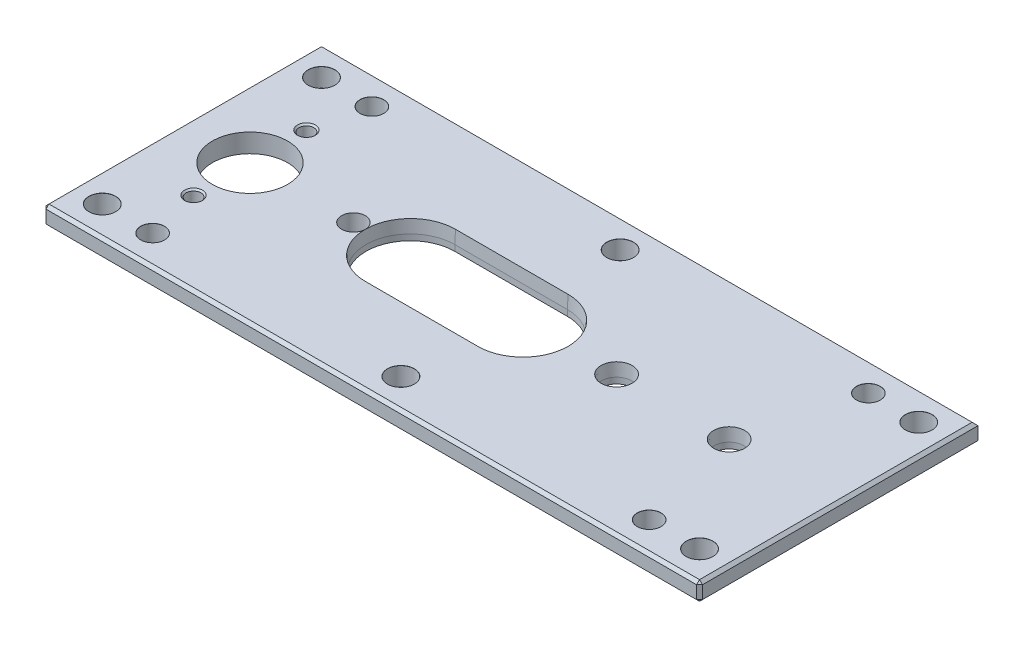
SolidWorks part; units mm, degrees
material "1.2316 (X36CrMo17)"
ref_plane "Front Plane" through (0, 0, 0) normal (0, 0, 1) x (1, 0, 0)
ref_plane "Top Plane" through (0, 0, 0) normal (0, 1, 0) x (1, 0, 0)
ref_plane "Right Plane" through (0, 0, 0) normal (1, 0, 0) x (0, 0, -1)
sketch "Sketch1" plane through (0, 0, 0) normal (0, 1, 0) x (1, 0, 0)
  line L1 (-110.8, 47) -> (110.8, 47)
  line L2 (-110.8, 47) -> (-110.8, -47)
  line L3 (-110.8, -47) -> (110.8, -47)
  line L4 (110.8, 47) -> (110.8, -47)
  line L5 (-110.8, 47) -> (110.8, -47) construction
  line L6 (-110.8, -47) -> (110.8, 47) construction
  point P0 (0, 0)
  dimension "D1" = 94
  dimension "D2" = 221.6
extrude "Boss-Extrude1" add sketch "Sketch1" against normal blind 6.35
sketch "Sketch2" plane through (0, 0, 0) normal (0, 1, 0) x (1, 0, 0)
  line L0 (-110.8, 0) -> (110.8, 0) construction
  line L1 (-110.8, 47) -> (-110.8, -47) construction
  line L2 (110.8, -47) -> (110.8, 47) construction
  line L3 (0, 47) -> (0, -47) construction
  line L4 (110.8, 47) -> (-110.8, 47) construction
  line L5 (-110.8, -47) -> (110.8, -47) construction
  line L6 (-33.8, 15) -> (4.2, 15)
  line L11 (-33.8, -15) -> (4.2, -15)
  line L12 (-48.8, 16.2329) -> (-48.8, -16.2329) construction
  line L13 (-50.4, 16.2329) -> (-50.4, -16.2329) construction
  line L14 (19.2, 15) -> (19.2, -15) construction
  line L15 (20.8, 15) -> (20.8, -15) construction
  arc A3 (-33.8, 15) -> (-33.8, -15) centre (-33.8, 0) ccw
  arc A4 (4.2, -15) -> (4.2, 15) centre (4.2, 0) ccw
  circle A5 centre (35.8, 0) radius 5
  circle A6 centre (73.8, 0) radius 5
  dimension "D1" = 15
  dimension "D3" = 10
  dimension "D2" = 38
  dimension "D4" = 38
  dimension "D5" = 62
  dimension "D6" = 69.6
  dimension "D7" = 1.6
  dimension "D8" = 1.6
sketch "Sketch3" plane through (0, 0, 0) normal (0, 1, 0) x (1, 0, 0)
  line L0 (-110.8, 0) -> (110.8, 0) construction
  line L1 (-50.4, 16.2329) -> (-50.4, -16.2329) construction
  circle A0 centre (-87.95, 0) radius 12.7
  circle A1 centre (-53.025, 0) radius 4
  dimension "D2" = 25.4
  dimension "D4" = 8
  dimension "D1" = 37.55
  dimension "D3" = 34.925
extrude "Cut-Extrude1" cut sketch "Sketch3" against normal up to next contours A1
chamfer "Chamfer1" distance 1 angle 45 11 edges at (0, 0, 47) (-110.8, 0, 0) (0, 0, -47) (110.8, 0, 0) (-110.8, -3.175, 47) (-110.8, -3.175, -47) (-110.8, -6.35, 0) (0, -6.35, -47) (110.8, -6.35, 0) (0, -6.35, 47) (110.8, -3.175, 47)
sketch "Sketch6" plane through (0, 0, 0) normal (0, 1, 0) x (1, 0, 0)
  line L0 (-33.8, 15) -> (4.2, 15) construction
  line L1 (-33.8, -15) -> (4.2, -15) construction
  line L2 (-33.8, 15) -> (4.2, 15)
  line L3 (-33.8, -15) -> (4.2, -15)
  circle A0 centre (73.8, 0) radius 5 construction
  circle A1 centre (35.8, 0) radius 5 construction
  arc A2 (-33.8, 15) -> (-33.8, -15) centre (-33.8, 0) ccw construction
  arc A3 (4.2, -15) -> (4.2, 15) centre (4.2, 0) ccw construction
  circle A4 centre (73.8, 0) radius 5
  circle A5 centre (35.8, 0) radius 5
  arc A6 (-33.8, 15) -> (-33.8, -15) centre (-33.8, 0) ccw
  arc A7 (4.2, -15) -> (4.2, 15) centre (4.2, 0) ccw
extrude "Cut-Extrude2" cut sketch "Sketch6" against normal through all
ref_plane "Plane1" through (-33.8, 0, 0) normal (1, 0, 0) x (0, 0, -1)
sketch "Sketch10" plane through (-33.8, 0, 0) normal (1, 0, 0) x (0, 0, -1)
  line L0 (15, -4.35) -> (15.228, 0)
  line L1 (15, -6.35) -> (15, 0) construction
  line L2 (51.7, 0) -> (-51.7, 0) construction
  line L3 (15, -4.35) -> (15, 0)
  line L4 (46, -6.35) -> (-46, -6.35) construction
  line L6 (15.228, 0) -> (15, 0)
  dimension "D1" = 3
  dimension "D2" = 2
sweep "Cut-Sweep1" cut profiles "Sketch10" path "Sketch2"
chamfer "Chamfer2" distance 4.35 angle 3 1 edges at (35.8, 0, 5)
chamfer "Chamfer3" distance 4.35 angle 3 1 edges at (73.8, 0, 5)
sketch "Sketch11" plane through (0, 0, 0) normal (0, 1, 0) x (1, 0, 0)
  circle A0 centre (-87.95, 0) radius 12.7 construction
  circle A1 centre (-87.95, 0) radius 12.7
extrude "Cut-Extrude3" cut sketch "Sketch11" against normal through all
sketch "Sketch12" plane through (0, 0, 0) normal (0, 1, 0) x (1, 0, 0)
  point P0 (-100.8, 37)
  point P3 (-100.8, -37)
  point P6 (100.8, 37)
  point P9 (100.8, -37)
  point P13 (0, 37)
  point P16 (0, -37)
hole_wizard "M8 Clearance Hole1" positions "Sketch12" profile "Sketch13" hole size "M8" standard "ISO" end condition through all
sketch "Sketch13" plane through (-100.8, 0, -37) normal (1, 0, 0) x (0, 0, 1)
  line L0 (0, 0) -> (0, 6.35)
  line L1 (0, 6.35) -> (4.525, 6.35)
  line L2 (4.5, 6.325) -> (4.5, 0.025)
  line L3 (4.5, 0.025) -> (4.525, 0)
  line L5 (4.525, 0) -> (0, 0)
  line L6 (-4.5, 0.025) -> (-4.525, 0) construction
  line L7 (4.525, 6.35) -> (4.5, 6.325)
  line L8 (-4.525, 6.35) -> (-4.5, 6.325) construction
  line L11 (0, -6.35) -> (0, 107.95) construction
  dimension "Thru Hole Dia." = 9
  dimension "Thru Hole Depth" = 6.35
  dimension "Near C'Sink Dia." = 9.05
  dimension "Near C'Sink Angle" = 90
  dimension "Far C'Sink Dia." = 9.05
  dimension "Far C'Sink Angle" = 90
sketch "Sketch14" plane through (0, 0, 0) normal (0, 1, 0) x (1, 0, 0)
  point P0 (-83.8, 37)
  point P3 (-83.8, -37)
  point P6 (83.8, 37)
  point P9 (83.8, -37)
hole_wizard "Ø8.0mm Dowel Hole1" positions "Sketch14" profile "Sketch15" hole size "Ø8.0" standard "ISO" end condition through all
sketch "Sketch15" plane through (-83.8, 0, -37) normal (1, 0, 0) x (0, 0, 1)
  line L0 (0, 0) -> (0, 6.35)
  line L1 (0, 6.35) -> (4.025, 6.35)
  line L2 (4, 6.325) -> (4, 0.025)
  line L3 (4, 0.025) -> (4.025, 0)
  line L5 (4.025, 0) -> (0, 0)
  line L6 (-4, 0.025) -> (-4.025, 0) construction
  line L7 (4.025, 6.35) -> (4, 6.325)
  line L8 (-4.025, 6.35) -> (-4, 6.325) construction
  line L11 (0, -6.35) -> (0, 107.95) construction
  dimension "Thru Hole Dia." = 8
  dimension "Thru Hole Depth" = 6.35
  dimension "Near C'Sink Dia." = 8.05
  dimension "Near C'Sink Angle" = 90
  dimension "Far C'Sink Dia." = 8.05
  dimension "Far C'Sink Angle" = 90
sketch "Sketch16" plane through (0, 0, 0) normal (0, 1, 0) x (1, 0, 0)
  point P0 (-87.95, 19.05)
  point P3 (-87.95, -19.05)
hole_wizard "M6 Tapped Hole1" positions "Sketch16" profile "Sketch17" tap size "M6" standard "ISO" end condition through all
sketch "Sketch17" plane through (-87.95, 0, -19.05) normal (1, 0, 0) x (0, 0, 1)
  line L0 (0, 0) -> (0, 6.35)
  line L1 (0, 6.35) -> (3.025, 6.35)
  line L2 (2.5, 5.825) -> (2.5, 0.525)
  line L3 (2.5, 0.525) -> (3.025, 0)
  line L5 (3.025, 0) -> (0, 0)
  line L6 (-2.5, 0.525) -> (-3.025, 0) construction
  line L7 (3.025, 6.35) -> (2.5, 5.825)
  line L8 (-3.025, 6.35) -> (-2.5, 5.825) construction
  line L11 (0, -6.35) -> (0, 107.95) construction
  dimension "Thru Tap Drill Dia." = 5
  dimension "Thru Tap Drill Depth" = 6.35
  dimension "Near C'Sink Dia." = 6.05
  dimension "Near C'Sink Angle" = 90
  dimension "Far C'Sink Dia." = 6.05
  dimension "Far C'Sink Angle" = 90
cosmetic thread "Hole Thread1" parameters "D2"=6
cosmetic thread "Hole Thread2" parameters "D2"=6
